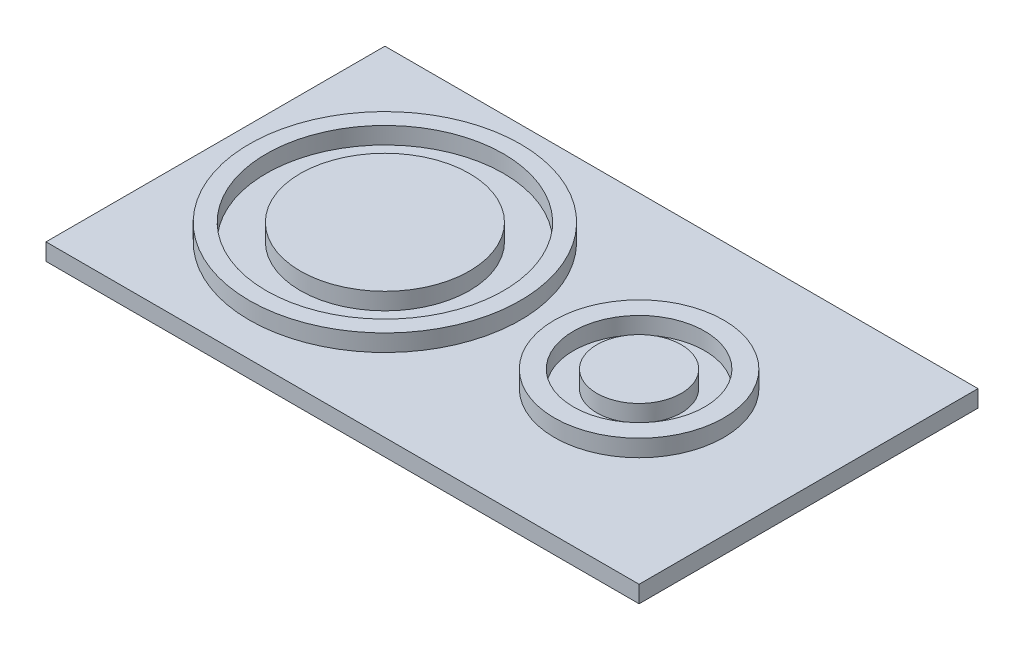
SolidWorks part; units mm, degrees
ref_plane "Alzado" through (0, 0, 0) normal (0, 0, 1) x (1, 0, 0)
ref_plane "Planta" through (0, 0, 0) normal (0, 1, 0) x (1, 0, 0)
ref_plane "Vista lateral" through (0, 0, 0) normal (1, 0, 0) x (0, 0, -1)
sketch "Croquis1" plane through (0, 0, 0) normal (0, 1, 0) x (1, 0, 0)
  line L1 (-35, -20) -> (35, -20)
  line L2 (-35, -20) -> (-35, 20)
  line L3 (-35, 20) -> (35, 20)
  line L4 (35, -20) -> (35, 20)
  line L5 (-35, -20) -> (35, 20) construction
  line L6 (-35, 20) -> (35, -20) construction
  point P0 (0, 0)
  dimension "D1" = 70
  dimension "D2" = 40
extrude "Saliente-Extruir1" add sketch "Croquis1" along normal blind 2
sketch "Croquis2" plane through (0, 2, 0) normal (0, 1, 0) x (1, 0, 0)
  circle A0 centre (-15, 0) radius 9.98
  circle A1 centre (-15, 0) radius 14
  circle A2 centre (-15, 0) radius 16
  circle A3 centre (15, 0) radius 4.98
  circle A4 centre (15, 0) radius 7.75
  circle A5 centre (15, 0) radius 10
  dimension "D1" = 19.96
  dimension "D2" = 28
  dimension "D3" = 32
  dimension "D5" = 20
  dimension "D6" = 9.96
  dimension "D7" = 15.5
  dimension "D4" = 15
  dimension "D8" = 15
extrude "Saliente-Extruir2" add sketch "Croquis2" along normal blind 2 contours A2 A1 | A3 | A5 | A4 | A0
